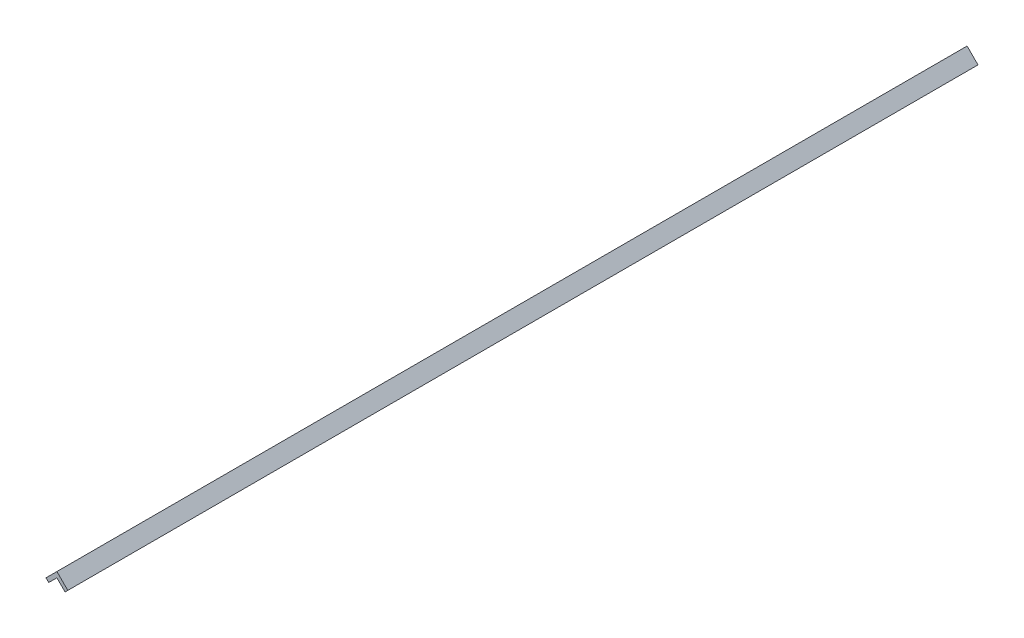
SolidWorks part; units mm, degrees
ref_plane "Plano frontal" through (0, 0, 0) normal (0, 0, 1) x (1, 0, 0)
ref_plane "Plano superior" through (0, 0, 0) normal (0, 1, 0) x (1, 0, 0)
ref_plane "Plano direito" through (0, 0, 0) normal (1, 0, 0) x (0, 0, -1)
sketch "Esboço1" plane through (0, 0, 0) normal (0, 0, 1) x (1, 0, 0)
  line L0 (0, 11.2289) -> (8.9803, 2.2486)
  line L1 (-8.9803, 2.2486) -> (-6.7317, 0)
  line L2 (0, 0) -> (0, 11.2289) construction
  line L3 (-6.7317, 0) -> (0, 6.7317)
  line L4 (8.9803, 2.2486) -> (6.7317, 0)
  line L5 (0, 11.2289) -> (-8.9803, 2.2486)
  line L6 (6.7317, 0) -> (0, 6.7317)
  dimension "D1" = 12.7
  dimension "D2" = 90
  dimension "D3" = 3.18
  dimension "D4" = 6.7317
sketch "Esboço2" plane through (0, 0, 0) normal (0, 1, 0) x (1, 0, 0)
  line L0 (0, -750) -> (0, 750)
  line L1 (0, 0) -> (-59.1058, 0) construction
  point P10 (498, 0)
  dimension "D2" = 750
sweep "Varredura1" add profiles "Esboço1" path "Esboço2"
